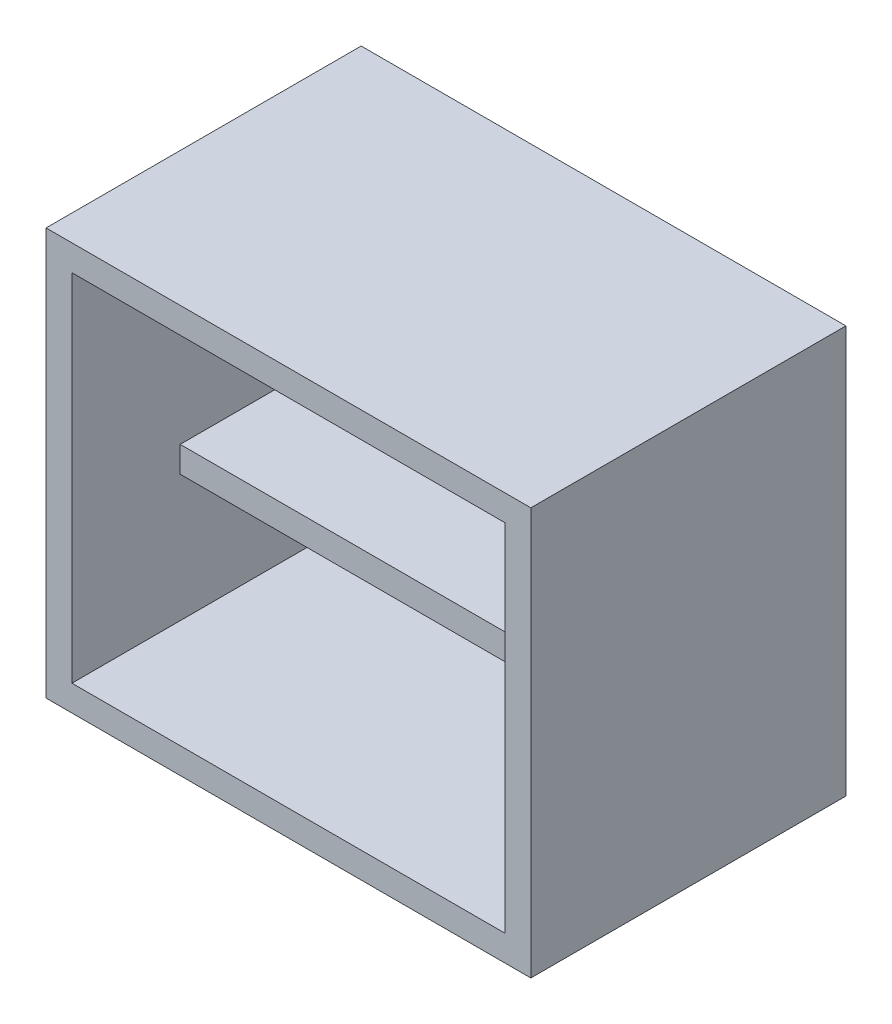
SolidWorks part; units mm, degrees
ref_plane "Alzado" through (0, 0, 0) normal (0, 0, 1) x (1, 0, 0)
ref_plane "Planta" through (0, 0, 0) normal (0, 1, 0) x (1, 0, 0)
ref_plane "Vista lateral" through (0, 0, 0) normal (1, 0, 0) x (0, 0, -1)
sketch "Croquis1" plane through (0, 0, 0) normal (0, 1, 0) x (1, 0, 0)
  line L1 (-150, -97.5) -> (150, -97.5)
  line L2 (-150, -97.5) -> (-150, 97.5)
  line L3 (-150, 97.5) -> (150, 97.5)
  line L4 (150, -97.5) -> (150, 97.5)
  line L5 (-150, -97.5) -> (150, 97.5) construction
  line L6 (-150, 97.5) -> (150, -97.5) construction
  point P0 (0, 0)
  dimension "D1" = 195
  dimension "D2" = 300
extrude "Saliente-Extruir1" add sketch "Croquis1" along normal blind 16
sketch "Croquis2" plane through (0, 16, 0) normal (0, 1, 0) x (1, 0, 0)
  line L0 (-150, -97.5) -> (150, -97.5) construction
  line L1 (-150, 97.5) -> (-134, 97.5)
  line L2 (-150, 97.5) -> (-150, -97.5)
  line L3 (-150, -97.5) -> (-134, -97.5)
  line L4 (-134, 97.5) -> (-134, -97.5)
  line L6 (150, 97.5) -> (134, 97.5)
  line L7 (150, 97.5) -> (150, -97.5)
  line L8 (150, -97.5) -> (134, -97.5)
  line L9 (134, 97.5) -> (134, -97.5)
  dimension "D1" = 16
  dimension "D2" = 16
extrude "Saliente-Extruir2" add sketch "Croquis2" along normal blind 220
sketch "Croquis7" plane through (0, 236, 0) normal (0, 1, 0) x (1, 0, 0)
  line L1 (-150, 97.5) -> (150, 97.5)
  line L2 (-150, 97.5) -> (-150, -97.5)
  line L3 (-150, -97.5) -> (150, -97.5)
  line L4 (150, 97.5) -> (150, -97.5)
extrude "Saliente-Extruir4" add sketch "Croquis7" along normal blind 16
ref_plane "Plano2" through (0, 94.5, 0) normal (0, 1, 0) x (1, 0, 0)
sketch "Croquis8" plane through (0, 94.5, 0) normal (0, 1, 0) x (1, 0, 0)
  line L7 (150, 97.5) -> (-150, 97.5) construction
  line L9 (-134, 97.5) -> (134, 97.5)
  line L10 (-134, 97.5) -> (-134, -30.5)
  line L11 (-134, -30.5) -> (134, -30.5)
  line L12 (134, 97.5) -> (134, -30.5)
  line L13 (150, -97.5) -> (150, 97.5) construction
  line L14 (-150, 97.5) -> (-150, -97.5) construction
  dimension "D1" = 128
  dimension "D2" = 16
  dimension "D3" = 16
extrude "Saliente-Extruir5" add sketch "Croquis8" along normal blind 16
sketch "Croquis11" plane through (0, 110.5, 0) normal (0, 1, 0) x (1, 0, 0)
  line L1 (31.3688, 81.987) -> (-9.6312, 81.987)
  line L2 (31.3688, 81.987) -> (31.3688, 46.987)
  line L3 (31.3688, 46.987) -> (-9.6312, 46.987)
  line L4 (-9.6312, 81.987) -> (-9.6312, 46.987)
  point P6 (0, 0)
  point P7 (0, 0)
  dimension "D1" = 41
  dimension "D2" = 35
extrude "Saliente-Extruir6" add sketch "Croquis11" along normal blind 20
